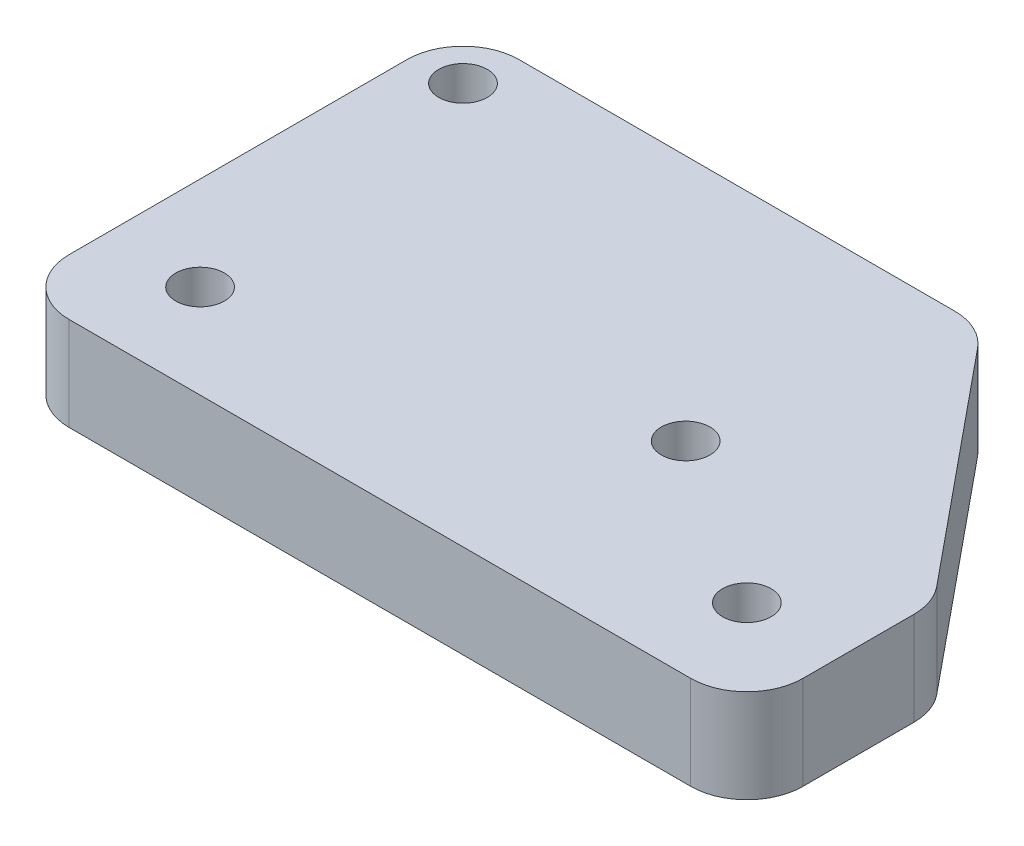
SolidWorks part; units mm, degrees
material "ﾎﾟﾘ塩化ﾋﾞﾆﾙ(PVC)硬質"
ref_plane "正面" through (0, 0, 0) normal (0, 0, 1) x (1, 0, 0)
ref_plane "平面" through (0, 0, 0) normal (0, 1, 0) x (1, 0, 0)
ref_plane "右側面" through (0, 0, 0) normal (1, 0, 0) x (0, 0, -1)
sketch "ｽｹｯﾁ1" plane through (0, 0, 0) normal (0, 1, 0) x (1, 0, 0)
  line L1 (-13.85, -7.9) -> (13.85, -7.9)
  line L2 (-13.85, -7.9) -> (-13.85, 7.9)
  line L3 (-13.85, 7.9) -> (13.85, 7.9)
  line L4 (13.85, -7.9) -> (13.85, 7.9)
  line L5 (-13.85, -7.9) -> (13.85, 7.9) construction
  line L6 (-13.85, 7.9) -> (13.85, -7.9) construction
  point P0 (0, 0)
  dimension "D1" = 15.8
  dimension "D2" = 27.7
extrude "ﾎﾞｽ - 押し出し1" add sketch "ｽｹｯﾁ1" along normal blind 5
sketch "ｽｹｯﾁ2" plane through (0, 5, 0) normal (0, 1, 0) x (1, 0, 0)
  line L0 (0, 0) -> (13.85, 0) construction
  line L1 (-11.25, -5.3) -> (11.25, -5.3) construction
  line L2 (-11.25, -5.3) -> (-11.25, 5.3) construction
  line L3 (-11.25, 5.3) -> (11.25, 5.3) construction
  line L4 (11.25, -5.3) -> (11.25, 5.3) construction
  line L5 (-11.25, -5.3) -> (11.25, 5.3) construction
  line L6 (-11.25, 5.3) -> (11.25, -5.3) construction
  line L7 (13.85, -7.9) -> (13.85, 7.9) construction
  circle A0 centre (-11.25, 5.3) radius 1.3
  circle A1 centre (11.25, -5.3) radius 1.3
  point P0 (0, 0)
  dimension "D3" = 2.6
  dimension "D1" = 22.5
  dimension "D2" = 10.6
extrude "ｶｯﾄ - 押し出し1" cut sketch "ｽｹｯﾁ2" against normal through all
sketch "ｽｹｯﾁ3" plane through (0, 5, 0) normal (0, 1, 0) x (1, 0, 0)
  line L1 (-8.85, -11.15) -> (20.37, -11.15) construction
  line L2 (-13.85, 7.9) -> (-13.85, -6.15)
  line L3 (-13.85, -6.15) -> (25.37, -6.15)
  line L4 (-13.85, -6.15) -> (-13.85, -16.15)
  line L5 (-13.85, -16.15) -> (25.37, -16.15)
  line L6 (25.37, -6.15) -> (25.37, -16.15)
  line L7 (-13.85, -6.15) -> (25.37, -16.15) construction
  line L8 (-13.85, -16.15) -> (25.37, -6.15) construction
  line L9 (13.85, 7.9) -> (25.37, -6.15)
  line L10 (13.85, 7.9) -> (13.85, -7.9)
  line L11 (13.85, -7.9) -> (-13.85, -7.9)
  line L12 (-13.85, -7.9) -> (-13.85, 7.9)
  circle A0 centre (20.37, -11.15) radius 1.3
  circle A1 centre (-8.85, -11.15) radius 1.3
  point P7 (5.76, -11.15)
  line M5 (13.85, -7.9) -> (13.85, 7.9)
  line M8 (-13.85, -7.9) -> (13.85, -7.9)
  dimension "D1" = 29.22
  dimension "D2" = 2.6
  dimension "D3" = 5
  dimension "D4" = 10
  dimension "D5" = 3.25
extrude "ﾎﾞｽ - 押し出し2" add sketch "ｽｹｯﾁ3" against normal up to surface (5 mm away) contours L6 L3 L4 L5 A0 A1 M5 M8 | L9 L3 M5 up to face at (-11.25, 0, -4)
fillet "ﾌｨﾚｯﾄ1" radius 3 5 edges at (-13.85, 2.5, -7.9) (13.85, 2.5, -7.9) (25.37, 2.5, 6.15) (25.37, 2.5, 16.15) (-13.85, 2.5, 16.15)
